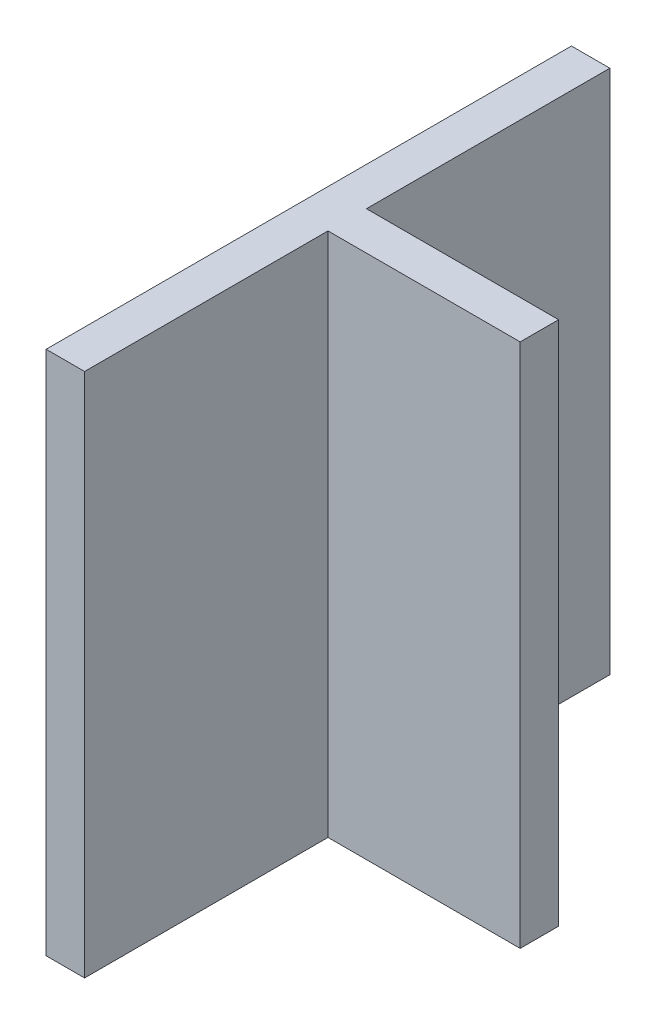
SolidWorks part; units mm, degrees
ref_plane "Front Plane" through (0, 0, 0) normal (0, 0, 1) x (1, 0, 0)
ref_plane "Top Plane" through (0, 0, 0) normal (0, 1, 0) x (1, 0, 0)
ref_plane "Right Plane" through (0, 0, 0) normal (1, 0, 0) x (0, 0, -1)
sketch "Sketch1" plane through (0, 0, 0) normal (0, 1, 0) x (1, 0, 0)
  line L1 (0, 20.5) -> (3, 20.5)
  line L2 (3, 20.5) -> (3, 1.5)
  line L3 (3, 1.5) -> (18, 1.5)
  line L4 (18, 1.5) -> (18, -1.5)
  line L5 (18, -1.5) -> (3, -1.5)
  line L6 (3, -1.5) -> (3, -20.5)
  line L7 (3, -20.5) -> (0, -20.5)
  line L9 (0, 20.5) -> (0, -20.5)
  point P0 (0, 0)
  dimension "D1" = 3
  dimension "D2" = 41
  dimension "D3" = 3
  dimension "D4" = 15
extrude "Boss-Extrude1" add sketch "Sketch1" along normal blind 41
